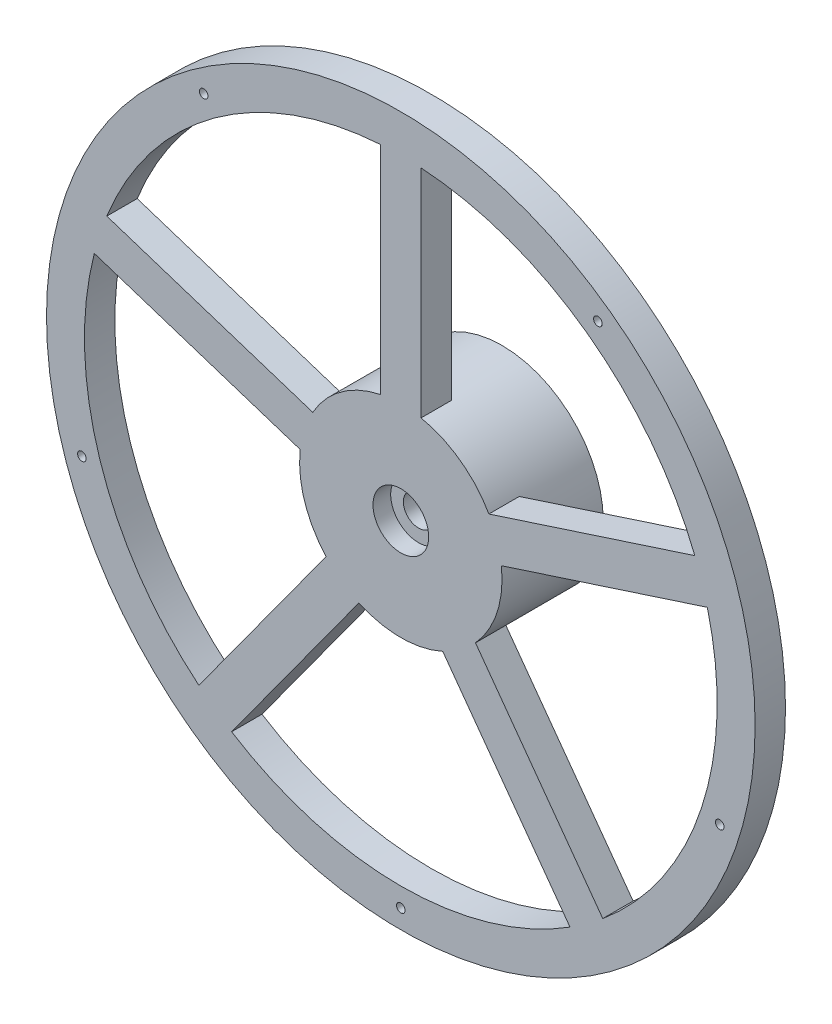
SolidWorks part; units mm, degrees
ref_plane "Front Plane" through (0, 0, 0) normal (0, 0, 1) x (1, 0, 0)
ref_plane "Top Plane" through (0, 0, 0) normal (0, 1, 0) x (1, 0, 0)
ref_plane "Right Plane" through (0, 0, 0) normal (1, 0, 0) x (0, 0, -1)
ref_plane "Plane_z28" through (0, 0, 28) normal (0, 0, 1) x (1, 0, 0)
sketch "Sketch1" plane through (0, 0, 28) normal (0, 0, 1) x (1, 0, 0)
  circle A0 centre (0, 0) radius 140
  circle A1 centre (0, 0) radius 125
extrude "Ring" add sketch "Sketch1" along normal blind 12
sketch "Sketch2" plane through (0, 0, 0) normal (0, 0, 1) x (1, 0, 0)
  circle A0 centre (0, 0) radius 40
extrude "Hub" add sketch "Sketch2" along normal blind 40
sketch "Sketch3" plane through (0, 0, 28) normal (0, 0, 1) x (1, 0, 0)
  line L0 (39.5633, 4.4432) -> (122.3053, 31.3277)
  line L1 (122.3053, 31.3277) -> (117.361, 46.5446)
  line L2 (117.361, 46.5446) -> (34.6191, 19.6601)
  line L3 (34.6191, 19.6601) -> (39.5633, 4.4432)
  line L4 (8, 39) -> (8, 126)
  line L5 (8, 126) -> (-8, 126)
  line L6 (-8, 126) -> (-8, 39)
  line L7 (-8, 39) -> (8, 39)
  line L8 (-34.6191, 19.6601) -> (-117.361, 46.5446)
  line L9 (-117.361, 46.5446) -> (-122.3053, 31.3277)
  line L10 (-122.3053, 31.3277) -> (-39.5633, 4.4432)
  line L11 (-39.5633, 4.4432) -> (-34.6191, 19.6601)
  line L12 (-29.3958, -26.8494) -> (-80.5331, -97.2339)
  line L13 (-80.5331, -97.2339) -> (-67.5888, -106.6384)
  line L14 (-67.5888, -106.6384) -> (-16.4515, -36.2539)
  line L15 (-16.4515, -36.2539) -> (-29.3958, -26.8494)
  line L16 (16.4515, -36.2539) -> (67.5888, -106.6384)
  line L17 (67.5888, -106.6384) -> (80.5331, -97.2339)
  line L18 (80.5331, -97.2339) -> (29.3958, -26.8494)
  line L19 (29.3958, -26.8494) -> (16.4515, -36.2539)
extrude "Spokes" add sketch "Sketch3" along normal blind 12
sketch "Sketch4" plane through (0, 0, 0) normal (0, 0, 1) x (1, 0, 0)
  circle A0 centre (0, 0) radius 6
extrude "Bore" cut sketch "Sketch4" along normal blind 40
sketch "Sketch5" plane through (0, 0, 0) normal (0, 0, 1) x (1, 0, 0)
  circle A0 centre (0, 0) radius 11
extrude "Bearing_seat_low" cut sketch "Sketch5" along normal blind 7
ref_plane "Plane_z33" through (0, 0, 33) normal (0, 0, 1) x (1, 0, 0)
sketch "Sketch6" plane through (0, 0, 33) normal (0, 0, 1) x (1, 0, 0)
  circle A0 centre (0, 0) radius 11
extrude "Bearing_seat_high" cut sketch "Sketch6" along normal blind 7
sketch "Sketch7" plane through (0, 0, 28) normal (0, 0, 1) x (1, 0, 0)
  circle A0 centre (77.8815, 107.1948) radius 1.7
  circle A1 centre (-77.8815, 107.1948) radius 1.7
  circle A2 centre (-126.015, -40.9448) radius 1.7
  circle A3 centre (0, -132.5) radius 1.7
  circle A4 centre (126.015, -40.9448) radius 1.7
extrude "Ring_screws" cut sketch "Sketch7" along normal blind 12
sketch "Sketch8" plane through (0, 0, 0) normal (0, 0, 1) x (1, 0, 0)
  circle A0 centre (21.2132, 21.2132) radius 1.25
  circle A1 centre (-21.2132, 21.2132) radius 1.25
  circle A2 centre (-21.2132, -21.2132) radius 1.25
  circle A3 centre (21.2132, -21.2132) radius 1.25
extrude "Grommet_screws" cut sketch "Sketch8" along normal blind 8
